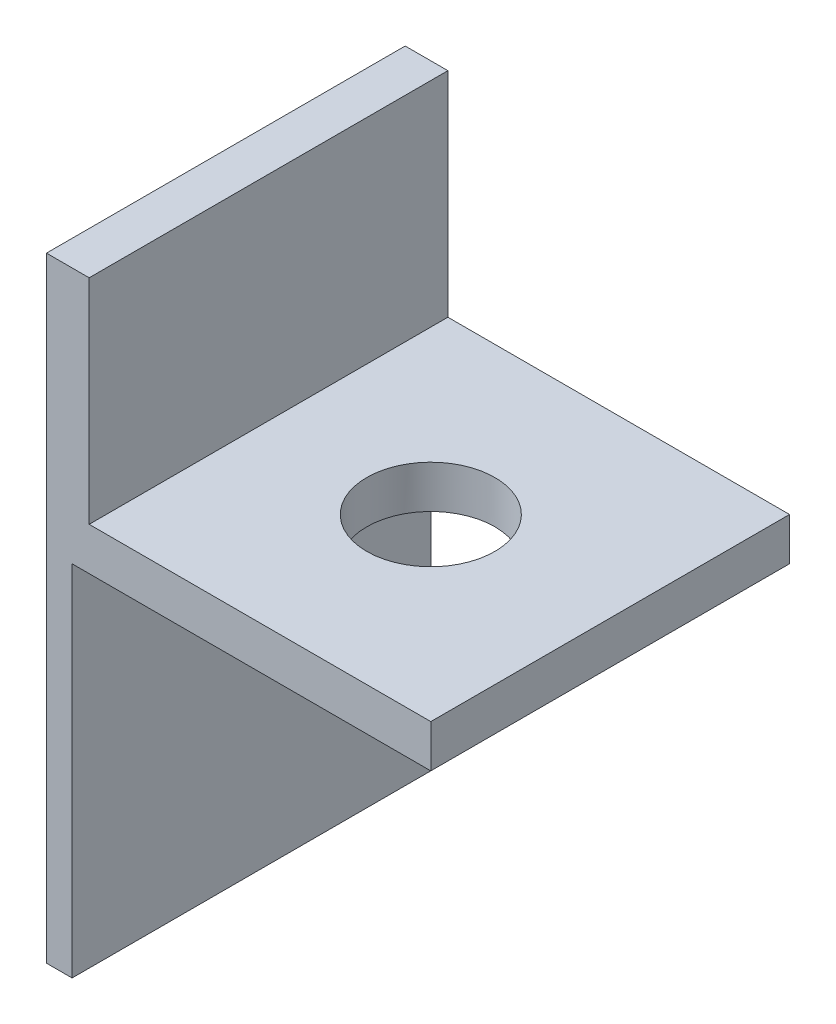
SolidWorks part; units mm, degrees
ref_plane "前视基准面" through (0, 0, 0) normal (0, 0, 1) x (1, 0, 0)
ref_plane "上视基准面" through (0, 0, 0) normal (0, 1, 0) x (1, 0, 0)
ref_plane "右视基准面" through (0, 0, 0) normal (1, 0, 0) x (0, 0, -1)
other "Configuration Table"
sketch "草图1" plane through (0, 0, 0) normal (0, 1, 0) x (1, 0, 0)
  line L1 (-21, -21) -> (21, -21)
  line L2 (-21, -21) -> (-21, 21)
  line L3 (-21, 21) -> (21, 21)
  line L4 (21, -21) -> (21, 21)
  line L5 (-21, -21) -> (21, 21) construction
  line L6 (-21, 21) -> (21, -21) construction
  point P0 (0, 0)
  dimension "D1" = 42
  dimension "D2" = 42
extrude "凸台-拉伸1" add sketch "草图1" along normal blind 5
sketch "草图2" plane through (-21, 0, 0) normal (-1, 0, 0) x (0, 0, 1)
  line L4 (-21, 0) -> (21, 0)
  line L5 (21, 0) -> (21, 5)
  line L6 (21, 5) -> (-21, 5)
  line L7 (-21, 5) -> (-21, 0)
  line L8 (-21, 0) -> (21, 0)
  line L9 (21, 0) -> (21, 5)
  line L10 (21, 5) -> (-21, 5)
  line L11 (-21, 5) -> (-21, 0)
  dimension "D1" = 0
extrude "凸台-拉伸2" add sketch "草图2" along normal blind 3
sketch "草图4" plane through (0, 5, 0) normal (0, 1, 0) x (1, 0, 0)
  line L0 (-19, 21) -> (-19, -21)
  line L4 (21, -21) -> (21, 21)
  line L5 (21, 21) -> (-24, 21)
  line L6 (-24, 21) -> (-24, -21)
  line L7 (-24, -21) -> (21, -21)
  line L8 (21, -21) -> (21, 21)
  line L9 (21, 21) -> (-24, 21)
  line L10 (-24, 21) -> (-24, -21)
  line L11 (-24, -21) -> (21, -21)
  line M7 (21, 21) -> (-24, 21)
  line M8 (-24, 21) -> (-24, -21)
  line M9 (-24, -21) -> (21, -21)
  dimension "D2" = 5
  dimension "D1" = 0
extrude "凸台-拉伸3" add sketch "草图4" along normal blind 25 contours L0 M7 M8 M9
sketch "草图5" plane through (0, 0, 0) normal (0, -1, 0) x (1, 0, 0)
  line L0 (-21, 21) -> (-21, -21)
  line L4 (21, -21) -> (21, 21)
  line L5 (21, 21) -> (-24, 21)
  line L6 (-24, 21) -> (-24, -21)
  line L7 (-24, -21) -> (21, -21)
  line L8 (21, -21) -> (21, 21)
  line L9 (21, 21) -> (-24, 21)
  line L10 (-24, 21) -> (-24, -21)
  line L11 (-24, -21) -> (21, -21)
  line M7 (21, 21) -> (-24, 21)
  line M8 (-24, 21) -> (-24, -21)
  line M9 (-24, -21) -> (21, -21)
  dimension "D2" = 3
  dimension "D1" = 0
extrude "凸台-拉伸4" add sketch "草图5" along normal blind 42 contours L0 M7 M8 M9
sketch "草图8" plane through (0, 5, 0) normal (0, 1, 0) x (1, 0, 0)
  circle A0 centre (0, 0) radius 7.5
  dimension "D1" = 15
extrude "切除-拉伸1" cut sketch "草图8" against normal blind 25
sketch "草图9" plane through (-19, 0, 0) normal (1, 0, 0) x (0, 0, -1)
  line L0 (-21, 30) -> (21, 5) construction
  line L1 (21, 30) -> (-21, 5) construction
  line L2 (0, 17.5) -> (0, 0) construction
